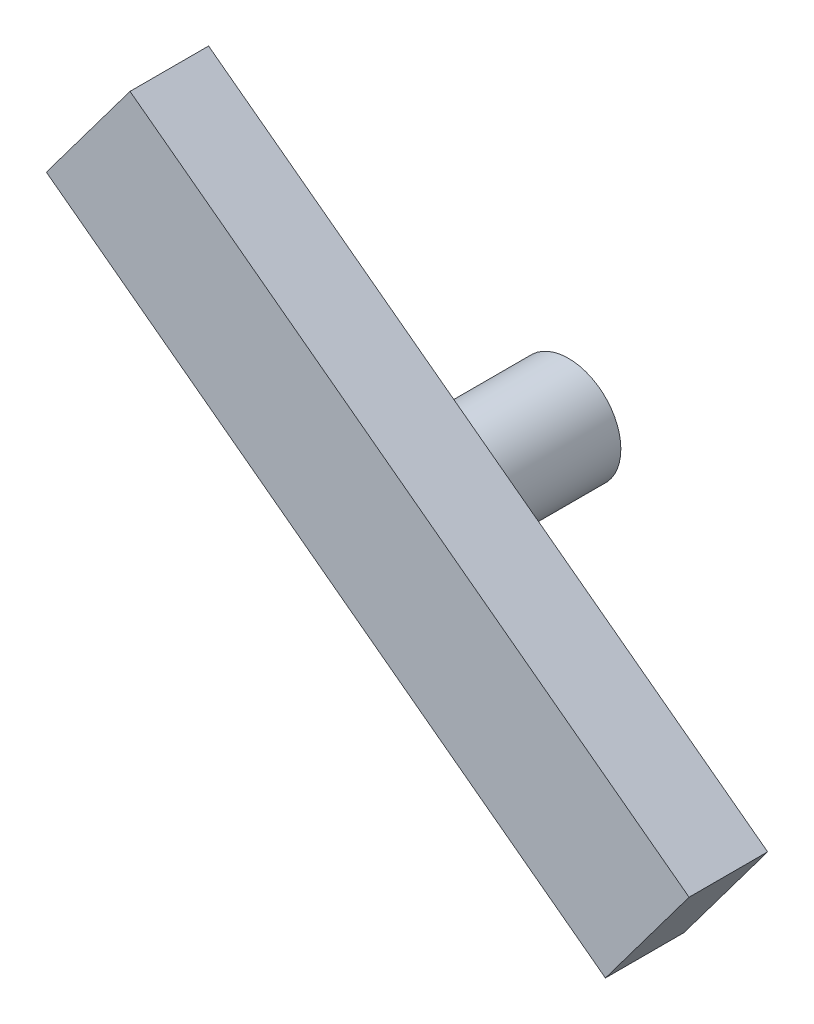
SolidWorks part; units mm, degrees
material "NEOPRENO"
ref_plane "Alzado" through (0, 0, 0) normal (0, 0, 1) x (1, 0, 0)
ref_plane "Planta" through (0, 0, 0) normal (0, 1, 0) x (1, 0, 0)
ref_plane "Vista lateral" through (0, 0, 0) normal (1, 0, 0) x (0, 0, -1)
sketch3d "Sk_Vastago"
  line L0 (-263.1284, 316.5049, -22) -> (-263.1284, 316.5049, -15)
sweep "Vastago" add path "Sk_Vastago" circular profile diameter 6 parameters "D3"=6
sketch "Sk_Goma" plane through (0, 0, 0) normal (0, 0, 1) x (1, 0, 0)
  line L0 (-249.5118, 301.3198) -> (-244.7188, 307.725)
  line L1 (-244.7188, 307.725) -> (-276.7449, 331.6901)
  line L2 (-276.7449, 331.6901) -> (-281.538, 325.2848)
  line L3 (-281.538, 325.2848) -> (-249.5118, 301.3198)
extrude "Goma" add sketch "Sk_Goma" along normal blind 4.5 from offset 15
